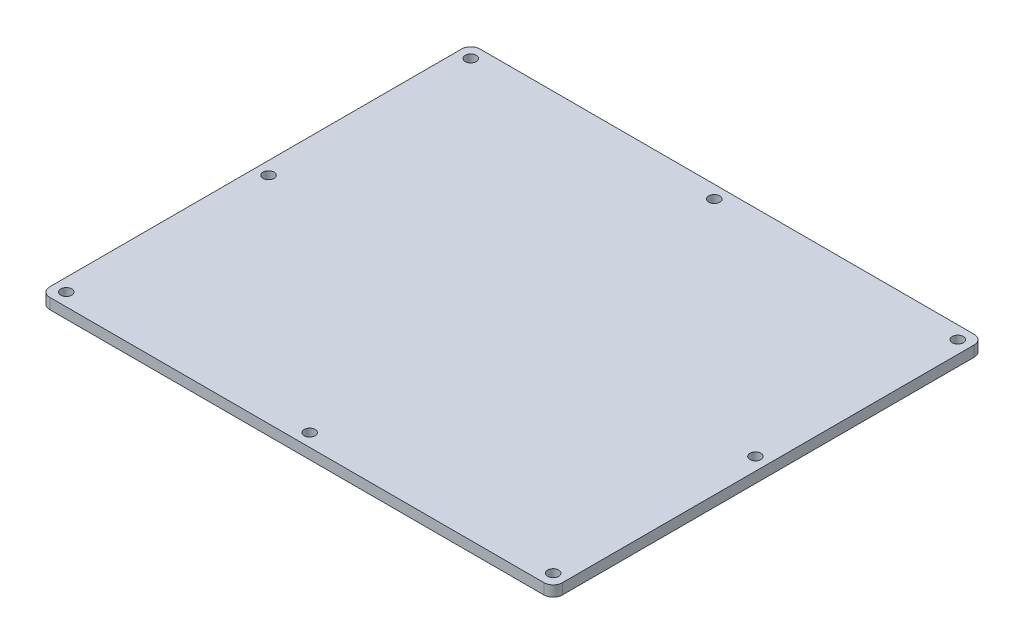
SolidWorks part; units mm, degrees
ref_plane "Front Plane" through (0, 0, 0) normal (0, 0, 1) x (1, 0, 0)
ref_plane "Top Plane" through (0, 0, 0) normal (0, 1, 0) x (1, 0, 0)
ref_plane "Right Plane" through (0, 0, 0) normal (1, 0, 0) x (0, 0, -1)
sketch "Sketch1" plane through (0, 0, 0) normal (0, 1, 0) x (1, 0, 0)
  line L0 (0, 0) -> (266, 0) construction
  line L1 (266, 0) -> (266, 221) construction
  line L2 (266, 221) -> (0, 221) construction
  line L3 (0, 221) -> (0, 0) construction
  line L5 (-2, 228) -> (268, 228)
  line L6 (-7, 223) -> (-7, -2)
  line L7 (-2, -7) -> (268, -7)
  line L8 (273, 223) -> (273, -2)
  circle A0 centre (0, 221) radius 3
  circle A1 centre (266, 221) radius 3
  circle A2 centre (266, 110.5) radius 3
  circle A3 centre (0, 110.5) radius 3
  circle A4 centre (133, 221) radius 3
  circle A5 centre (133, 0) radius 3
  circle A6 centre (266, 0) radius 3
  circle A7 centre (0, 0) radius 3
  arc A8 (-7, 223) -> (-2, 228) centre (-2, 223) cw
  arc A9 (268, 228) -> (273, 223) centre (268, 223) cw
  arc A10 (268, -7) -> (273, -2) centre (268, -2) ccw
  arc A11 (-7, -2) -> (-2, -7) centre (-2, -2) ccw
  point P29 (133, 0)
  point P30 (133, 0)
  point P31 (133, 221)
  point P32 (266, 110.5)
  point P33 (0, 110.5)
  dimension "D5" = 6
  dimension "D14" = 5
  dimension "D15" = 5
  dimension "D16" = 5
  dimension "D17" = 5
  dimension "D2" = 7
  dimension "D3" = 235
  dimension "D4" = 280
  dimension "D11" = 7
  dimension "D12" = 7
  dimension "D13" = 7
extrude "Boss-Extrude1" add sketch "Sketch1" along normal blind 5.842
